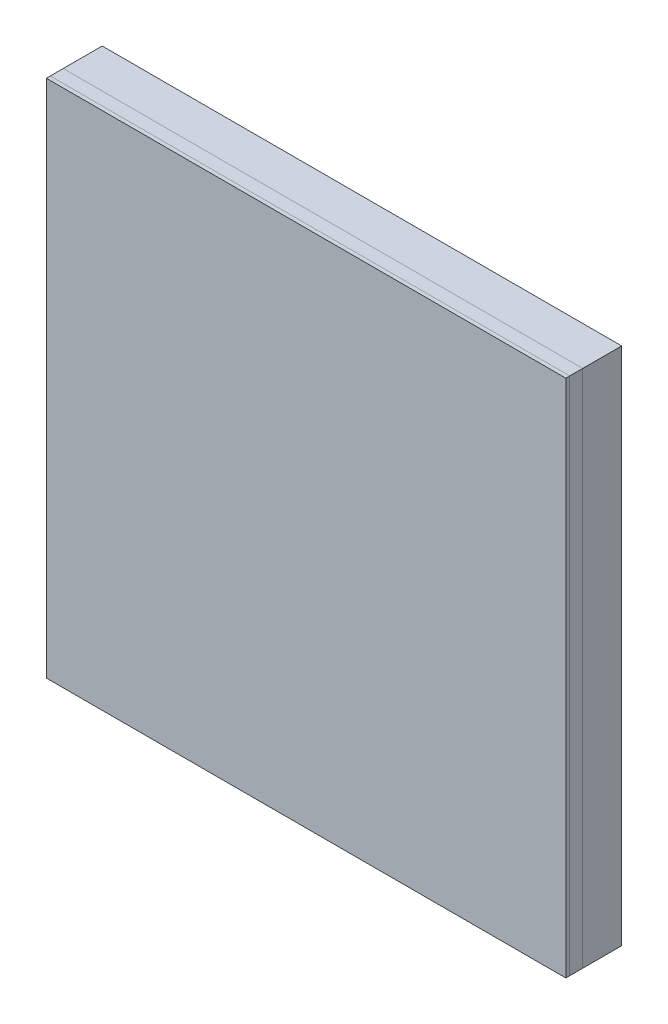
SolidWorks part; units mm, degrees
ref_plane "前视基准面" through (0, 0, 0) normal (0, 0, 1) x (1, 0, 0)
ref_plane "上视基准面" through (0, 0, 0) normal (0, 1, 0) x (1, 0, 0)
ref_plane "右视基准面" through (0, 0, 0) normal (1, 0, 0) x (0, 0, -1)
sketch "草图1" plane through (0, 0, 0) normal (0, 0, 1) x (1, 0, 0)
  line L1 (0, 4) -> (-4, 4)
  line L2 (-4, 4) -> (-4, -4)
  line L3 (-4, -4) -> (4, -4)
  line L4 (4, -4) -> (4, 4)
  line L5 (4, 4) -> (0, 4)
extrude "陶瓷基板" add sketch "草图1" along normal blind 0.6
sketch "草图2" plane through (0, 0, 0) normal (0, 0, 1) x (1, 0, 0)
  line L0 (-3.6, 3.9) -> (-3.9, 3.6)
  line L1 (-3.9, 0) -> (-3.9, 2.65)
  line L2 (-3.9, 2.65) -> (3.9, 2.65)
  line L3 (3.9, 2.65) -> (3.9, -2.65)
  line L4 (3.9, -2.65) -> (-3.9, -2.65)
  line L5 (-3.9, -2.65) -> (-3.9, 0)
  line L6 (-3.9, 3.25) -> (3.9, 3.25)
  line L7 (3.9, 3.25) -> (3.9, 3.9)
  line L8 (3.9, 3.9) -> (-3.6, 3.9)
  line L9 (-3.9, 3.6) -> (-3.9, 3.25)
  line L10 (-3.9, -3.9) -> (-3.9, -3.25)
  line L11 (3.9, -3.9) -> (-3.9, -3.9)
  line L12 (3.9, -3.25) -> (3.9, -3.9)
  line L13 (-3.9, -3.25) -> (3.9, -3.25)
  point P10 (-3.9, 3.9)
extrude "底部焊盘" add sketch "草图2" against normal blind 0.065 from surface at 0 separate body starting at face at (0, 0, 0)
sketch "三安55mil焊盘参考" plane through (0, 0, 0) normal (0, 0, 1) x (1, 0, 0)
  line L6 (2.7919, 0.1149) -> (2.7919, 0.6459)
  line L7 (-0.0254, 0.0254) -> (-0.0254, 1.4224)
  line L8 (-0.0254, 1.4224) -> (-1.4224, 1.4224)
  line L9 (-1.4224, 1.4224) -> (-1.4224, 0.0254)
  line L10 (-1.4224, 0.0254) -> (-0.0254, 0.0254)
  line L11 (-1.3419, 1.3329) -> (-0.1029, 1.3329)
  line L12 (1.5529, 0.1149) -> (2.7919, 0.1149)
  line L13 (-0.1029, 1.3329) -> (-0.1029, 0.7809)
  line L16 (-0.1029, 0.7809) -> (-1.3419, 0.7809)
  line L17 (-1.3419, 0.7809) -> (-1.3419, 1.3329)
  line L18 (-1.3419, 0.6459) -> (-0.1029, 0.6459)
  line L19 (-0.1029, 0.6459) -> (-0.1029, 0.1149)
  line L20 (-0.1029, 0.1149) -> (-1.3419, 0.1149)
  line L21 (-1.3419, 0.1149) -> (-1.3419, 0.6459)
  line L22 (1.5529, 0.6459) -> (1.5529, 0.1149)
  line L23 (-1.4754, 0.0254) -> (-1.4754, 1.4224)
  line L24 (-1.4754, 1.4224) -> (-2.8724, 1.4224)
  line L25 (-2.8724, 1.4224) -> (-2.8724, 0.0254)
  line L26 (-2.8724, 0.0254) -> (-1.4754, 0.0254)
  line L27 (-2.7919, 1.3329) -> (-1.5529, 1.3329)
  line L28 (-1.5529, 1.3329) -> (-1.5529, 0.7809)
  line L29 (-1.5529, 0.7809) -> (-2.7919, 0.7809)
  line L30 (-2.7919, 0.7809) -> (-2.7919, 1.3329)
  line L31 (-2.7919, 0.6459) -> (-1.5529, 0.6459)
  line L32 (-1.5529, 0.6459) -> (-1.5529, 0.1149)
  line L33 (-1.5529, 0.1149) -> (-2.7919, 0.1149)
  line L34 (-2.7919, 0.1149) -> (-2.7919, 0.6459)
  line L37 (2.7919, 0.6459) -> (1.5529, 0.6459)
  line L38 (2.7919, 0.7809) -> (2.7919, 1.3329)
  line L39 (1.5529, 0.7809) -> (2.7919, 0.7809)
  line L40 (1.5529, 1.3329) -> (1.5529, 0.7809)
  line L41 (2.7919, 1.3329) -> (1.5529, 1.3329)
  line L42 (2.8724, 0.0254) -> (1.4754, 0.0254)
  line L43 (2.8724, 1.4224) -> (2.8724, 0.0254)
  line L44 (1.4754, 1.4224) -> (2.8724, 1.4224)
  line L45 (1.4754, 0.0254) -> (1.4754, 1.4224)
  line L46 (1.3419, 0.1149) -> (1.3419, 0.6459)
  line L47 (0.1029, 0.1149) -> (1.3419, 0.1149)
  line L48 (0.1029, 0.6459) -> (0.1029, 0.1149)
  line L49 (1.3419, 0.6459) -> (0.1029, 0.6459)
  line L50 (1.3419, 0.7809) -> (1.3419, 1.3329)
  line L51 (0.1029, 0.7809) -> (1.3419, 0.7809)
  line L52 (0.1029, 1.3329) -> (0.1029, 0.7809)
  line L53 (1.3419, 1.3329) -> (0.1029, 1.3329)
  line L54 (1.4224, 0.0254) -> (0.0254, 0.0254)
  line L55 (1.4224, 1.4224) -> (1.4224, 0.0254)
  line L56 (0.0254, 1.4224) -> (1.4224, 1.4224)
  line L57 (0.0254, 0.0254) -> (0.0254, 1.4224)
  line L58 (0.0254, 2.8702) -> (0.0254, 1.4732)
  line L59 (0.0254, 1.4732) -> (1.4224, 1.4732)
  line L60 (1.4224, 1.4732) -> (1.4224, 2.8702)
  line L61 (1.4224, 2.8702) -> (0.0254, 2.8702)
  line L62 (1.3419, 1.5627) -> (0.1029, 1.5627)
  line L63 (0.1029, 1.5627) -> (0.1029, 2.1147)
  line L64 (0.1029, 2.1147) -> (1.3419, 2.1147)
  line L65 (1.3419, 2.1147) -> (1.3419, 1.5627)
  line L66 (1.3419, 2.2497) -> (0.1029, 2.2497)
  line L67 (0.1029, 2.2497) -> (0.1029, 2.7807)
  line L68 (0.1029, 2.7807) -> (1.3419, 2.7807)
  line L69 (1.3419, 2.7807) -> (1.3419, 2.2497)
  line L70 (1.4754, 2.8702) -> (1.4754, 1.4732)
  line L71 (1.4754, 1.4732) -> (2.8724, 1.4732)
  line L72 (2.8724, 1.4732) -> (2.8724, 2.8702)
  line L73 (2.8724, 2.8702) -> (1.4754, 2.8702)
  line L74 (2.7919, 1.5627) -> (1.5529, 1.5627)
  line L75 (1.5529, 1.5627) -> (1.5529, 2.1147)
  line L76 (1.5529, 2.1147) -> (2.7919, 2.1147)
  line L77 (2.7919, 2.1147) -> (2.7919, 1.5627)
  line L78 (2.7919, 2.2497) -> (1.5529, 2.2497)
  line L79 (-2.7919, 2.7807) -> (-2.7919, 2.2497)
  line L80 (-1.5529, 2.7807) -> (-2.7919, 2.7807)
  line L81 (-1.5529, 2.2497) -> (-1.5529, 2.7807)
  line L82 (-2.7919, 2.2497) -> (-1.5529, 2.2497)
  line L83 (-2.7919, 2.1147) -> (-2.7919, 1.5627)
  line L84 (-1.5529, 2.1147) -> (-2.7919, 2.1147)
  line L85 (-1.5529, 1.5627) -> (-1.5529, 2.1147)
  line L86 (-2.7919, 1.5627) -> (-1.5529, 1.5627)
  line L87 (-2.8724, 2.8702) -> (-1.4754, 2.8702)
  line L88 (-2.8724, 1.4732) -> (-2.8724, 2.8702)
  line L89 (-1.4754, 1.4732) -> (-2.8724, 1.4732)
  line L90 (-1.4754, 2.8702) -> (-1.4754, 1.4732)
  line L91 (1.5529, 2.2497) -> (1.5529, 2.7807)
  line L92 (-1.3419, 2.7807) -> (-1.3419, 2.2497)
  line L93 (-0.1029, 2.7807) -> (-1.3419, 2.7807)
  line L94 (-0.1029, 2.2497) -> (-0.1029, 2.7807)
  line L95 (-1.3419, 2.2497) -> (-0.1029, 2.2497)
  line L96 (-1.3419, 2.1147) -> (-1.3419, 1.5627)
  line L97 (-0.1029, 2.1147) -> (-1.3419, 2.1147)
  line L98 (-0.1029, 1.5627) -> (-0.1029, 2.1147)
  line L99 (1.5529, 2.7807) -> (2.7919, 2.7807)
  line L100 (-1.3419, 1.5627) -> (-0.1029, 1.5627)
  line L101 (-1.4224, 2.8702) -> (-0.0254, 2.8702)
  line L102 (-1.4224, 1.4732) -> (-1.4224, 2.8702)
  line L103 (-0.0254, 1.4732) -> (-1.4224, 1.4732)
  line L104 (-0.0254, 2.8702) -> (-0.0254, 1.4732)
  line L105 (2.7919, 2.7807) -> (2.7919, 2.2497)
  line L107 (2.7919, -2.7807) -> (2.7919, -2.2497)
  line L108 (-0.0254, -2.8702) -> (-0.0254, -1.4732)
  line L109 (-0.0254, -1.4732) -> (-1.4224, -1.4732)
  line L110 (-1.4224, -1.4732) -> (-1.4224, -2.8702)
  line L111 (-1.4224, -2.8702) -> (-0.0254, -2.8702)
  line L112 (-1.3419, -1.5627) -> (-0.1029, -1.5627)
  line L113 (1.5529, -2.7807) -> (2.7919, -2.7807)
  line L114 (-0.1029, -1.5627) -> (-0.1029, -2.1147)
  line L115 (-0.1029, -2.1147) -> (-1.3419, -2.1147)
  line L116 (-1.3419, -2.1147) -> (-1.3419, -1.5627)
  line L117 (-1.3419, -2.2497) -> (-0.1029, -2.2497)
  line L118 (-0.1029, -2.2497) -> (-0.1029, -2.7807)
  line L119 (-0.1029, -2.7807) -> (-1.3419, -2.7807)
  line L120 (-1.3419, -2.7807) -> (-1.3419, -2.2497)
  line L121 (1.5529, -2.2497) -> (1.5529, -2.7807)
  line L122 (-1.4754, -2.8702) -> (-1.4754, -1.4732)
  line L123 (-1.4754, -1.4732) -> (-2.8724, -1.4732)
  line L124 (-2.8724, -1.4732) -> (-2.8724, -2.8702)
  line L125 (-2.8724, -2.8702) -> (-1.4754, -2.8702)
  line L126 (-2.7919, -1.5627) -> (-1.5529, -1.5627)
  line L127 (-1.5529, -1.5627) -> (-1.5529, -2.1147)
  line L128 (-1.5529, -2.1147) -> (-2.7919, -2.1147)
  line L129 (-2.7919, -2.1147) -> (-2.7919, -1.5627)
  line L130 (-2.7919, -2.2497) -> (-1.5529, -2.2497)
  line L131 (-1.5529, -2.2497) -> (-1.5529, -2.7807)
  line L132 (-1.5529, -2.7807) -> (-2.7919, -2.7807)
  line L133 (-2.7919, -2.7807) -> (-2.7919, -2.2497)
  line L134 (2.7919, -2.2497) -> (1.5529, -2.2497)
  line L135 (2.7919, -2.1147) -> (2.7919, -1.5627)
  line L136 (1.5529, -2.1147) -> (2.7919, -2.1147)
  line L137 (1.5529, -1.5627) -> (1.5529, -2.1147)
  line L138 (2.7919, -1.5627) -> (1.5529, -1.5627)
  line L139 (2.8724, -2.8702) -> (1.4754, -2.8702)
  line L140 (2.8724, -1.4732) -> (2.8724, -2.8702)
  line L141 (1.4754, -1.4732) -> (2.8724, -1.4732)
  line L142 (1.4754, -2.8702) -> (1.4754, -1.4732)
  line L143 (1.3419, -2.7807) -> (1.3419, -2.2497)
  line L144 (0.1029, -2.7807) -> (1.3419, -2.7807)
  line L145 (0.1029, -2.2497) -> (0.1029, -2.7807)
  line L146 (1.3419, -2.2497) -> (0.1029, -2.2497)
  line L147 (1.3419, -2.1147) -> (1.3419, -1.5627)
  line L148 (0.1029, -2.1147) -> (1.3419, -2.1147)
  line L149 (0.1029, -1.5627) -> (0.1029, -2.1147)
  line L150 (1.3419, -1.5627) -> (0.1029, -1.5627)
  line L151 (1.4224, -2.8702) -> (0.0254, -2.8702)
  line L152 (1.4224, -1.4732) -> (1.4224, -2.8702)
  line L153 (0.0254, -1.4732) -> (1.4224, -1.4732)
  line L154 (0.0254, -2.8702) -> (0.0254, -1.4732)
  line L155 (0.0254, -0.0254) -> (0.0254, -1.4224)
  line L156 (0.0254, -1.4224) -> (1.4224, -1.4224)
  line L157 (1.4224, -1.4224) -> (1.4224, -0.0254)
  line L158 (1.4224, -0.0254) -> (0.0254, -0.0254)
  line L159 (1.3419, -1.3329) -> (0.1029, -1.3329)
  line L160 (0.1029, -1.3329) -> (0.1029, -0.7809)
  line L161 (0.1029, -0.7809) -> (1.3419, -0.7809)
  line L162 (1.3419, -0.7809) -> (1.3419, -1.3329)
  line L163 (1.3419, -0.6459) -> (0.1029, -0.6459)
  line L164 (0.1029, -0.6459) -> (0.1029, -0.1149)
  line L165 (0.1029, -0.1149) -> (1.3419, -0.1149)
  line L166 (1.3419, -0.1149) -> (1.3419, -0.6459)
  line L167 (1.4754, -0.0254) -> (1.4754, -1.4224)
  line L168 (1.4754, -1.4224) -> (2.8724, -1.4224)
  line L169 (2.8724, -1.4224) -> (2.8724, -0.0254)
  line L170 (2.8724, -0.0254) -> (1.4754, -0.0254)
  line L171 (2.7919, -1.3329) -> (1.5529, -1.3329)
  line L172 (1.5529, -1.3329) -> (1.5529, -0.7809)
  line L173 (1.5529, -0.7809) -> (2.7919, -0.7809)
  line L174 (2.7919, -0.7809) -> (2.7919, -1.3329)
  line L175 (2.7919, -0.6459) -> (1.5529, -0.6459)
  line L176 (-2.7919, -0.1149) -> (-2.7919, -0.6459)
  line L177 (-1.5529, -0.1149) -> (-2.7919, -0.1149)
  line L178 (-1.5529, -0.6459) -> (-1.5529, -0.1149)
  line L179 (-2.7919, -0.6459) -> (-1.5529, -0.6459)
  line L180 (-2.7919, -0.7809) -> (-2.7919, -1.3329)
  line L181 (-1.5529, -0.7809) -> (-2.7919, -0.7809)
  line L182 (-1.5529, -1.3329) -> (-1.5529, -0.7809)
  line L183 (-2.7919, -1.3329) -> (-1.5529, -1.3329)
  line L184 (-2.8724, -0.0254) -> (-1.4754, -0.0254)
  line L185 (-2.8724, -1.4224) -> (-2.8724, -0.0254)
  line L186 (-1.4754, -1.4224) -> (-2.8724, -1.4224)
  line L187 (-1.4754, -0.0254) -> (-1.4754, -1.4224)
  line L188 (1.5529, -0.6459) -> (1.5529, -0.1149)
  line L189 (-1.3419, -0.1149) -> (-1.3419, -0.6459)
  line L190 (-0.1029, -0.1149) -> (-1.3419, -0.1149)
  line L191 (-0.1029, -0.6459) -> (-0.1029, -0.1149)
  line L192 (-1.3419, -0.6459) -> (-0.1029, -0.6459)
  line L193 (-1.3419, -0.7809) -> (-1.3419, -1.3329)
  line L194 (-0.1029, -0.7809) -> (-1.3419, -0.7809)
  line L195 (-0.1029, -1.3329) -> (-0.1029, -0.7809)
  line L196 (1.5529, -0.1149) -> (2.7919, -0.1149)
  line L197 (-1.3419, -1.3329) -> (-0.1029, -1.3329)
  line L198 (-1.4224, -0.0254) -> (-0.0254, -0.0254)
  line L199 (-1.4224, -1.4224) -> (-1.4224, -0.0254)
  line L200 (-0.0254, -1.4224) -> (-1.4224, -1.4224)
  line L201 (-0.0254, -0.0254) -> (-0.0254, -1.4224)
  line L202 (2.7919, -0.1149) -> (2.7919, -0.6459)
  dimension "D1" = 2
sketch "草图4" plane through (0, 0, 0) normal (0, 0, 1) x (1, 0, 0)
  line L0 (2.7919, 2.7807) -> (2.6419, 2.7807)
  line L2 (1.5529, 2.7807) -> (2.7919, 2.7807) construction
  line L3 (-3.9, 3.9) -> (3.9, 3.9)
  line L4 (2.7919, 2.2497) -> (3.9, 2.2497)
  line L5 (3.9, 3.9) -> (3.9, 2.2497)
  line L6 (2.7919, 2.2497) -> (-3.9, 2.2497)
  line L7 (-3.9, 2.2497) -> (-3.9, 3.9)
  line L8 (2.6419, 2.7807) -> (2.6419, 2.8807)
  line L9 (2.7919, 2.6307) -> (2.8919, 2.6307)
  line L10 (2.7919, 2.7807) -> (2.7919, 2.6307)
  line L11 (2.7919, 2.7807) -> (2.7919, 2.2497) construction
  line L12 (2.8919, 2.6307) -> (2.8919, 2.8807)
  line L13 (2.8919, 2.8807) -> (2.6419, 2.8807)
  line L14 (-3.9, -3.5491) -> (-3.55, -3.8991)
  line L16 (-2.8919, 2.8807) -> (-2.6419, 2.8807)
  line L17 (-2.8919, 2.6307) -> (-2.8919, 2.8807)
  line L18 (-2.7919, 2.7807) -> (-2.7919, 2.6307)
  line L19 (-2.7919, 2.6307) -> (-2.8919, 2.6307)
  line L20 (-2.6419, 2.7807) -> (-2.6419, 2.8807)
  line L21 (-2.7919, 2.7807) -> (-2.6419, 2.7807)
  line L23 (-2.7919, -2.7798) -> (-2.6419, -2.7798)
  line L24 (-2.6419, -2.7798) -> (-2.6419, -2.8798)
  line L25 (-2.7919, -2.6298) -> (-2.8919, -2.6298)
  line L26 (-2.7919, -2.7798) -> (-2.7919, -2.6298)
  line L27 (-2.8919, -2.6298) -> (-2.8919, -2.8798)
  line L28 (-2.8919, -2.8798) -> (-2.6419, -2.8798)
  line L29 (2.8919, -2.8798) -> (2.6419, -2.8798)
  line L30 (2.8919, -2.6298) -> (2.8919, -2.8798)
  line L31 (2.7919, -2.7798) -> (2.7919, -2.6298)
  line L32 (2.7919, -2.6298) -> (2.8919, -2.6298)
  line L33 (2.6419, -2.7798) -> (2.6419, -2.8798)
  line L34 (-3.9, -2.2488) -> (-3.9, -3.5491)
  line L35 (2.7919, -2.2488) -> (-3.9, -2.2488)
  line L36 (3.9, -3.5491) -> (3.9, -2.2488)
  line L37 (2.7919, -2.2488) -> (3.9, -2.2488)
  line L38 (-3.55, -3.8991) -> (3.55, -3.8991)
  line L39 (2.7919, -2.7798) -> (2.6419, -2.7798)
  line L40 (3.55, -3.8991) -> (3.9, -3.5491)
  line L41 (-2.7919, -2.1147) -> (-3.9, -2.1147)
  line L42 (-2.7919, -2.1147) -> (3.9, -2.1147)
  line L43 (2.7919, -0.7809) -> (3.9, -0.7809)
  line L44 (3.9, -0.7809) -> (3.9, -2.1147)
  line L45 (2.7919, -0.7809) -> (-3.9, -0.7809)
  line L46 (-3.9, -0.7809) -> (-3.9, -2.1147)
  line L47 (-2.7919, -0.6459) -> (-3.9, -0.6459)
  line L48 (-2.7919, -0.6459) -> (3.9, -0.6459)
  line L49 (2.7919, 0.6459) -> (3.9, 0.6459)
  line L50 (3.9, 0.6459) -> (3.9, -0.6459)
  line L51 (2.7919, 0.6459) -> (-3.9, 0.6459)
  line L52 (-3.9, 0.6459) -> (-3.9, -0.6459)
  line L53 (-2.7919, 0.7809) -> (-3.9, 0.7809)
  line L54 (-2.7919, 2.1147) -> (-3.9, 2.1147)
  line L55 (-3.9, 2.1147) -> (-3.9, 0.7809)
  line L56 (-2.7919, 2.1147) -> (3.9, 2.1147)
  line L57 (3.9, 2.1147) -> (3.9, 0.7809)
  line L58 (3.9, 0.7809) -> (-2.7919, 0.7809)
  point P42 (-3.9, -3.8991)
  point P44 (3.9, -3.8991)
extrude "顶层铜线路" add sketch "草图4" along normal blind 0.065 from surface at 0.6 separate body starting at face at (0, 0, 0.6)
sketch "草图7" plane through (0, 0, 0) normal (0, 0, 1) x (1, 0, 0)
  line L0 (3.9, -0.6459) -> (-3.9, -0.6459) construction
  line L1 (-3.9, 3.9) -> (3.9, 3.9)
  line L2 (-3.9, 3.9) -> (-3.9, 2.2497)
  line L3 (-3.9, 2.2497) -> (3.9, 2.2497)
  line L4 (3.9, 3.9) -> (3.9, 2.2497)
  line L5 (3.9, 2.1147) -> (-3.9, 2.1147)
  line L6 (3.9, 2.1147) -> (3.9, 0.7806)
  line L7 (3.9, 0.7806) -> (-3.9, 0.7806)
  line L8 (-3.9, 2.1147) -> (-3.9, 0.7806)
  line L9 (-3.9, 0.6459) -> (3.9, 0.6459)
  line L10 (-3.9, 0.6459) -> (-3.9, -0.6459)
  line L11 (-3.9, -0.6459) -> (3.9, -0.6459)
  line L12 (3.9, 0.6459) -> (3.9, -0.6459)
  line L13 (3.9, -2.1147) -> (-3.9, -2.1147) construction
  line L14 (3.9, -0.7809) -> (-3.9, -0.7809)
  line L15 (3.9, -0.7809) -> (3.9, -2.1147)
  line L16 (3.9, -2.1147) -> (-3.9, -2.1147)
  line L17 (-3.9, -0.7809) -> (-3.9, -2.1147)
  line L18 (-3.9, -3.5491) -> (-3.9, -2.2488)
  line L19 (-3.9, -2.2488) -> (3.9, -2.2488)
  line L20 (-3.9, -2.2488) -> (3.9, -2.2488) construction
  line L21 (3.9, -2.2488) -> (3.9, -3.5491)
  line L22 (3.9, -3.5491) -> (3.55, -3.8991) construction
  line L23 (3.9, -3.5491) -> (3.55, -3.8991)
  line L24 (3.55, -3.8991) -> (-3.55, -3.8991)
  line L25 (-3.55, -3.8991) -> (-3.9, -3.5491)
  line L27 (-4, 4) -> (4, 4)
  line L28 (-4, 4) -> (-4, -4)
  line L29 (-4, -4) -> (4, -4)
  line L30 (4, 4) -> (4, -4)
extrude "陶瓷板线路填缝胶水" add sketch "草图7" along normal up to surface (0.065 mm away) from surface at 0.6 separate body up to face at (2.7752, -2.7631, 0.665) starting at face at (0, 0, 0.6)
sketch "草图9" plane through (0, 0, 0) normal (0, 0, 1) x (1, 0, 0)
  line L1 (-2.8724, 2.8702) -> (-1.4754, 2.8702)
  line L2 (-2.8724, 2.8702) -> (-2.8724, 1.4732)
  line L3 (-2.8724, 1.4732) -> (-1.4754, 1.4732)
  line L4 (-1.4754, 2.8702) -> (-1.4754, 1.4732)
  line L5 (-1.4224, 2.8702) -> (-0.0254, 2.8702)
  line L6 (-1.4224, 2.8702) -> (-1.4224, 1.4732)
  line L7 (-1.4224, 1.4732) -> (-0.0254, 1.4732)
  line L8 (-0.0254, 2.8702) -> (-0.0254, 1.4732)
  line L9 (0.0254, 1.4732) -> (1.4224, 1.4732)
  line L10 (0.0254, 1.4732) -> (0.0254, 2.8702)
  line L11 (0.0254, 2.8702) -> (1.4224, 2.8702)
  line L12 (1.4224, 1.4732) -> (1.4224, 2.8702)
  line L13 (1.4754, 2.8702) -> (2.8724, 2.8702)
  line L14 (1.4754, 2.8702) -> (1.4754, 1.4732)
  line L15 (1.4754, 1.4732) -> (2.8724, 1.4732)
  line L16 (2.8724, 2.8702) -> (2.8724, 1.4732)
  line L17 (2.8724, 1.4224) -> (1.4754, 1.4224)
  line L18 (2.8724, 1.4224) -> (2.8724, 0.0254)
  line L19 (2.8724, 0.0254) -> (1.4754, 0.0254)
  line L20 (1.4754, 1.4224) -> (1.4754, 0.0254)
  line L21 (1.4754, -0.0254) -> (2.8724, -0.0254)
  line L22 (1.4754, -0.0254) -> (1.4754, -1.4224)
  line L23 (1.4754, -1.4224) -> (2.8724, -1.4224)
  line L24 (2.8724, -0.0254) -> (2.8724, -1.4224)
  line L25 (1.4754, -1.4732) -> (2.8724, -1.4732)
  line L26 (1.4754, -1.4732) -> (1.4754, -2.8702)
  line L27 (1.4754, -2.8702) -> (2.8724, -2.8702)
  line L28 (2.8724, -1.4732) -> (2.8724, -2.8702)
  line L29 (1.4224, -1.4732) -> (0.0254, -1.4732)
  line L30 (1.4224, -1.4732) -> (1.4224, -2.8702)
  line L31 (1.4224, -2.8702) -> (0.0254, -2.8702)
  line L32 (0.0254, -1.4732) -> (0.0254, -2.8702)
  line L33 (1.4224, -1.4224) -> (0.0254, -1.4224)
  line L34 (1.4224, -1.4224) -> (1.4224, -0.0254)
  line L35 (1.4224, -0.0254) -> (0.0254, -0.0254)
  line L36 (0.0254, -1.4224) -> (0.0254, -0.0254)
  line L37 (0.0254, 0.0254) -> (1.4224, 0.0254)
  line L38 (0.0254, 0.0254) -> (0.0254, 1.4224)
  line L39 (0.0254, 1.4224) -> (1.4224, 1.4224)
  line L40 (1.4224, 0.0254) -> (1.4224, 1.4224)
  line L41 (-0.0254, 1.4224) -> (-1.4224, 1.4224)
  line L42 (-0.0254, 1.4224) -> (-0.0254, 0.0254)
  line L43 (-0.0254, 0.0254) -> (-1.4224, 0.0254)
  line L44 (-1.4224, 1.4224) -> (-1.4224, 0.0254)
  line L45 (-1.4224, -0.0254) -> (-0.0254, -0.0254)
  line L46 (-1.4224, -0.0254) -> (-1.4224, -1.4224)
  line L47 (-1.4224, -1.4224) -> (-0.0254, -1.4224)
  line L48 (-0.0254, -0.0254) -> (-0.0254, -1.4224)
  line L49 (-0.0254, -1.4732) -> (-1.4224, -1.4732)
  line L50 (-0.0254, -1.4732) -> (-0.0254, -2.8702)
  line L51 (-0.0254, -2.8702) -> (-1.4224, -2.8702)
  line L52 (-1.4224, -1.4732) -> (-1.4224, -2.8702)
  line L53 (-1.4754, -2.8702) -> (-2.8724, -2.8702)
  line L54 (-1.4754, -2.8702) -> (-1.4754, -1.4732)
  line L55 (-1.4754, -1.4732) -> (-2.8724, -1.4732)
  line L56 (-2.8724, -2.8702) -> (-2.8724, -1.4732)
  line L57 (-2.8724, -1.4224) -> (-1.4754, -1.4224)
  line L58 (-2.8724, -1.4224) -> (-2.8724, -0.0254)
  line L59 (-2.8724, -0.0254) -> (-1.4754, -0.0254)
  line L60 (-1.4754, -1.4224) -> (-1.4754, -0.0254)
  line L61 (-1.4754, 0.0254) -> (-2.8724, 0.0254)
  line L62 (-1.4754, 0.0254) -> (-1.4754, 1.4224)
  line L63 (-1.4754, 1.4224) -> (-2.8724, 1.4224)
  line L64 (-2.8724, 0.0254) -> (-2.8724, 1.4224)
extrude "三安55e核心" add sketch "草图9" along normal blind 0.135 from surface at 0.665 separate body starting at face at (-2.7752, 2.764, 0.665)
sketch "草图10" plane through (0, 0, 0) normal (0, 0, 1) x (1, 0, 0)
  line L0 (-1.4754, 2.8702) -> (-1.4224, 2.8702)
  line L1 (-1.4224, 2.8702) -> (-1.4224, 1.4732)
  line L2 (-1.4224, 1.4732) -> (-0.0254, 1.4732)
  line L3 (-0.0254, 1.4732) -> (-0.0254, 2.8702)
  line L4 (-0.0254, 2.8702) -> (0.0254, 2.8702)
  line L5 (0.0254, 2.8702) -> (0.0254, 1.4732)
  line L6 (0.0254, 1.4732) -> (1.4224, 1.4732)
  line L7 (1.4224, 1.4732) -> (1.4224, 2.8702)
  line L8 (1.4224, 2.8702) -> (1.4754, 2.8702)
  line L9 (1.4754, 2.8702) -> (1.4754, 1.4732)
  line L10 (1.4754, 1.4732) -> (2.8724, 1.4732)
  line L11 (2.8724, 1.4732) -> (2.8724, 1.4224)
  line L12 (2.8724, 1.4224) -> (1.4754, 1.4224)
  line L13 (1.4754, 1.4224) -> (1.4754, 0.0254)
  line L14 (1.4754, 0.0254) -> (2.8724, 0.0254)
  line L15 (2.8724, 0.0254) -> (2.8724, -0.0254)
  line L16 (2.8724, -0.0254) -> (1.4754, -0.0254)
  line L17 (1.4754, -0.0254) -> (1.4754, -1.4224)
  line L18 (1.4754, -1.4224) -> (2.8724, -1.4224)
  line L19 (2.8724, -1.4224) -> (2.8724, -1.4732)
  line L20 (2.8724, -1.4732) -> (1.4754, -1.4732)
  line L21 (1.4754, -1.4732) -> (1.4754, -2.8702)
  line L22 (1.4754, -2.8702) -> (1.4224, -2.8702)
  line L23 (1.4224, -2.8702) -> (1.4224, -1.4732)
  line L24 (1.4224, -1.4732) -> (0.0254, -1.4732)
  line L25 (0.0254, -1.4732) -> (0.0254, -2.8702)
  line L26 (0.0254, -2.8702) -> (-0.0254, -2.8702)
  line L27 (-0.0254, -2.8702) -> (-0.0254, -1.4732)
  line L28 (-0.0254, -1.4732) -> (-1.4224, -1.4732)
  line L29 (-1.4224, -1.4732) -> (-1.4224, -2.8702)
  line L30 (-1.4224, -2.8702) -> (-1.4754, -2.8702)
  line L31 (-1.4754, -2.8702) -> (-1.4754, -1.4732)
  line L32 (-1.4754, -1.4732) -> (-2.8724, -1.4732)
  line L33 (-2.8724, -1.4732) -> (-2.8724, -1.4224)
  line L34 (-2.8724, -1.4224) -> (-1.4754, -1.4224)
  line L35 (-1.4754, -1.4224) -> (-1.4754, -0.0254)
  line L36 (-1.4754, -0.0254) -> (-2.8724, -0.0254)
  line L37 (-2.8724, -0.0254) -> (-2.8724, 0.0254)
  line L38 (-2.8724, 0.0254) -> (-1.4754, 0.0254)
  line L39 (-1.4754, 0.0254) -> (-1.4754, 1.4224)
  line L40 (-1.4754, 1.4224) -> (-2.8724, 1.4224)
  line L41 (-2.8724, 1.4224) -> (-2.8724, 1.4732)
  line L42 (-2.8724, 1.4732) -> (-1.4754, 1.4732)
  line L43 (-1.4754, 1.4732) -> (-1.4754, 2.8702)
  line L45 (-1.4224, 1.4224) -> (-0.0254, 1.4224)
  line L46 (-1.4224, 1.4224) -> (-1.4224, 0.0254)
  line L47 (-1.4224, 0.0254) -> (-0.0254, 0.0254)
  line L48 (-0.0254, 1.4224) -> (-0.0254, 0.0254)
  line L49 (1.4224, 1.4224) -> (0.0254, 1.4224)
  line L50 (1.4224, 1.4224) -> (1.4224, 0.0254)
  line L51 (1.4224, 0.0254) -> (0.0254, 0.0254)
  line L52 (0.0254, 1.4224) -> (0.0254, 0.0254)
  line L53 (1.4224, -0.0254) -> (0.0254, -0.0254)
  line L54 (1.4224, -0.0254) -> (1.4224, -1.4224)
  line L55 (1.4224, -1.4224) -> (0.0254, -1.4224)
  line L56 (0.0254, -0.0254) -> (0.0254, -1.4224)
  line L57 (-0.0254, -1.4224) -> (-1.4224, -1.4224)
  line L58 (-0.0254, -1.4224) -> (-0.0254, -0.0254)
  line L59 (-0.0254, -0.0254) -> (-1.4224, -0.0254)
  line L60 (-1.4224, -1.4224) -> (-1.4224, -0.0254)
extrude "核心填缝胶水" add sketch "草图10" along normal blind 0.135 from surface at 0.665 separate body starting at face at (0, 1.4478, 0.665)
sketch "草图11" plane through (0, 0, 0) normal (0, 0, 1) x (1, 0, 0)
  line L1 (-2.8724, 2.8702) -> (2.8724, 2.8702)
  line L2 (-2.8724, 2.8702) -> (-2.8724, -2.8702)
  line L3 (-2.8724, -2.8702) -> (2.8724, -2.8702)
  line L4 (2.8724, 2.8702) -> (2.8724, -2.8702)
  line L5 (4, -4) -> (-4, -4)
  line L6 (4, -4) -> (4, 4)
  line L7 (4, 4) -> (-4, 4)
  line L8 (-4, -4) -> (-4, 4)
extrude "核心外圈填缝胶水" add sketch "草图11" along normal up to surface (0.135 mm away) from surface at 0.665 up to face at (0.7239, -0.7239, 0.8) starting at face at (-2.7752, 2.764, 0.665)
sketch "草图12" plane through (0, 0, 0) normal (0, 0, 1) x (1, 0, 0)
  text T0 "35" font "Arial Rounded MT Bold" height 0.4
extrude "背部35字符" cut sketch "草图12" against normal up to surface (0.065 mm away) from surface at 0 up to face at (0, 0, -0.065) starting at face at (0, 0, 0)
sketch "草图13" plane through (0, 0, 0) normal (0, 0, 1) x (1, 0, 0)
  line L1 (-4, 4) -> (4, 4)
  line L2 (-4, 4) -> (-4, -4)
  line L3 (-4, -4) -> (4, -4)
  line L4 (4, 4) -> (4, -4)
extrude "荧光粉层" add sketch "草图13" along normal blind 0.06 from surface at 0.8 separate body starting at face at (-2.1739, 2.1717, 0.8)
